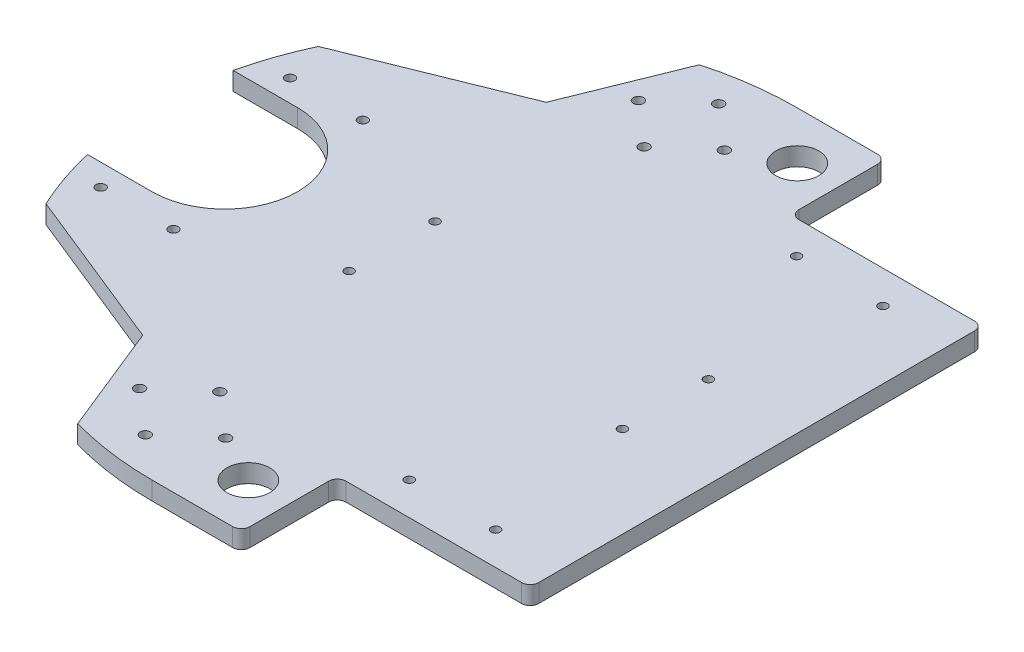
SolidWorks part; units mm, degrees
ref_plane "Front Plane" through (0, 0, 0) normal (0, 0, 1) x (1, 0, 0)
ref_plane "Top Plane" through (0, 0, 0) normal (0, 1, 0) x (1, 0, 0)
ref_plane "Right Plane" through (0, 0, 0) normal (1, 0, 0) x (0, 0, -1)
sketch "Sketch1" plane through (0, 0, 0) normal (0, 1, 0) x (1, 0, 0)
  line L0 (0, -112.5) -> (0, 0) construction
  line L1 (-3.175, 112.5) -> (95.25, 112.5)
  line L3 (-3.175, -112.5) -> (95.25, -112.5)
  line L4 (95.25, 112.5) -> (95.25, -112.5)
  line L5 (0, 0) -> (0, 112.5) construction
  arc A0 (-3.175, 112.5) -> (-3.175, -112.5) centre (-3.175, 0) ccw
  dimension "D1" = 95.25
  dimension "D4" = 112.5
  dimension "D2" = 3.175
  dimension "D3" = 225
extrude "Boss-Extrude1" add sketch "Sketch1" against normal blind 6.35
sketch "Sketch8" plane through (0, 0, 0) normal (0, 1, 0) x (1, 0, 0)
  line L0 (-3.175, 112.5) -> (-3.175, -112.5) construction
  line L1 (-115.675, 0) -> (95.25, 0) construction
  line L2 (95.25, -112.5) -> (95.25, 112.5) construction
  line L3 (-90.2716, 25.4) -> (-229.7767, 25.4)
  line L4 (-229.7767, 25.4) -> (-229.7767, -25.4)
  line L5 (-229.7767, -25.4) -> (-90.2716, -25.4)
  line L6 (-105.3846, 12.065) -> (-105.3846, -12.065) construction
  line L7 (-105.3846, -12.065) -> (-75.1586, -12.065) construction
  line L8 (-75.1586, -12.065) -> (-75.1586, 12.065) construction
  line L9 (-75.1586, 12.065) -> (-105.3846, 12.065) construction
  arc A0 (-3.175, 112.5) -> (-3.175, -112.5) centre (-3.175, 0) ccw construction
  circle A1 centre (-100.5586, 33.02) radius 1.651
  arc A2 (-90.2716, 25.4) -> (-90.2716, -25.4) centre (-90.2716, 0) cw
  circle A3 centre (-100.5586, -33.02) radius 1.651
  circle A4 centre (-75.1586, 33.02) radius 1.651
  circle A5 centre (-75.1586, -33.02) radius 1.651
  point P12 (-3.175, 0)
  point P19 (-75.1586, 0)
  point P22 (-90.2716, 12.065)
  dimension "D2" = 87.0966
  dimension "D1" = 25.4
  dimension "D6" = 33.02
  dimension "D11" = 3.302
  dimension "D3" = 112.5
  dimension "D4" = 30.226
  dimension "D5" = 24.13
  dimension "D7" = 33.02
  dimension "D8" = 33.02
  dimension "D9" = 33.02
  dimension "D10" = 25.4
extrude "Cut-Extrude5" cut sketch "Sketch8" against normal through all
sketch "Sketch9" plane through (0, 0, 0) normal (0, 1, 0) x (1, 0, 0)
  line L0 (-105.1513, 47.5087) -> (-48.5319, 70.3845)
  line L1 (-48.5319, 70.3845) -> (-12.2799, 160.1114)
  line L2 (-19.5468, 160.1114) -> (-135.6404, 160.1114)
  line L3 (-135.6404, 160.1114) -> (-135.6404, 47.5087)
  line L4 (-135.6404, 47.5087) -> (-105.1513, 47.5087)
  line L5 (-12.2799, 160.1114) -> (-19.5468, 160.1114)
  line L6 (-162.9335, 0) -> (171.6729, 0) construction
  line L7 (-105.1513, 0) -> (-105.1513, 47.5087) construction
  line L8 (-105.1513, 47.5087) -> (171.6729, 47.5087) construction
  line L9 (-48.5319, 70.3845) -> (171.6729, 70.3845) construction
  line L10 (-105.1513, -47.5087) -> (-48.5319, -70.3845)
  line L11 (-48.5319, -70.3845) -> (-12.2799, -160.1114)
  line L12 (-12.2799, -160.1114) -> (-135.6404, -160.1114)
  line L13 (-135.6404, -160.1114) -> (-135.6404, -47.5087)
  line L14 (-135.6404, -47.5087) -> (-105.1513, -47.5087)
  line L15 (-105.1513, -47.5087) -> (171.6729, -47.5087) construction
  line L16 (-48.5319, -70.3845) -> (171.6729, -70.3845) construction
  line L17 (-105.1513, -47.5087) -> (-105.1513, 0) construction
  arc A0 (-3.175, 112.5) -> (-112.7701, 25.4) centre (-3.175, 0) ccw construction
  arc A1 (-112.7701, -25.4) -> (-3.175, -112.5) centre (-3.175, 0) ccw construction
  dimension "D1" = 47.5087
  dimension "D2" = 22
  dimension "D3" = 68
  dimension "D4" = 22
  dimension "D5" = 68
extrude "Cut-Extrude6" cut sketch "Sketch9" against normal through all
sketch "Sketch16" plane through (0, 0, 0) normal (0, 1, 0) x (1, 0, 0)
  line L0 (-18, -100) -> (-18, -74) construction
  line L1 (-33, -87) -> (-3, -87) construction
  line L3 (-112.7701, 0) -> (95.25, 0) construction
  line L5 (95.25, -112.5) -> (95.25, 112.5) construction
  circle A0 centre (-33, -87) radius 1.775
  circle A1 centre (-18, -100) radius 1.775
  circle A2 centre (-18, -74) radius 1.775
  circle A3 centre (-3, -87) radius 1.775
  circle A4 centre (-33, 87) radius 1.775
  circle A5 centre (-18, 100) radius 1.775
  circle A6 centre (-18, 74) radius 1.775
  circle A7 centre (-3, 87) radius 1.775
  dimension "D3" = 3.55
  dimension "D1" = 26
  dimension "D2" = 30
  dimension "D4" = 87
  dimension "D5" = 113.25
extrude "Cut-Extrude9" cut sketch "Sketch16" against normal through all
sketch "Sketch17" plane through (0, 0, 0) normal (0, 1, 0) x (1, 0, 0)
  line L0 (95.25, 0) -> (-112.7701, 0) construction
  line L1 (95.25, 112.5) -> (27.98, 112.5)
  line L2 (95.25, 112.5) -> (95.25, 79)
  line L3 (95.25, 79) -> (27.98, 79)
  line L4 (27.98, 112.5) -> (27.98, 79)
  line L5 (95.25, -112.5) -> (27.98, -112.5)
  line L6 (95.25, -112.5) -> (95.25, -79)
  line L7 (95.25, -79) -> (27.98, -79)
  line L8 (27.98, -112.5) -> (27.98, -79)
  line L9 (95.25, -112.5) -> (95.25, 112.5) construction
  line L10 (41.62, -67.5582) -> (41.62, 67.5582) construction
  line L11 (41.62, 67.5582) -> (71.75, 67.5582) construction
  line L12 (71.75, 67.5582) -> (71.75, -67.5582) construction
  line L13 (71.75, -67.5582) -> (41.62, -67.5582) construction
  line L14 (27.98, 95.75) -> (95.25, 95.75) construction
  line L15 (27.98, -95.75) -> (95.25, -95.75) construction
  circle A0 centre (41.62, 67.5582) radius 1.55
  circle A1 centre (71.75, 67.5582) radius 1.55
  circle A2 centre (41.62, -67.5582) radius 1.55
  circle A3 centre (71.75, -67.5582) radius 1.55
  circle A4 centre (13.6873, 95.75) radius 7.5
  circle A5 centre (13.6873, -95.75) radius 7.5
  dimension "D4" = 3.1
  dimension "D5" = 15
  dimension "D1" = 33.5
  dimension "D2" = 30.13
  dimension "D3" = 23.5
extrude "Cut-Extrude10" cut sketch "Sketch17" against normal through all
fillet "Fillet1" radius 3 6 edges at (27.98, -3.175, -112.5) (27.98, -3.175, -79) (95.25, -3.175, -79) (95.25, -3.175, 79) (27.98, -3.175, 79) (27.98, -3.175, 112.5)
sketch "Sketch18" plane through (0, 0, 0) normal (0, 1, 0) x (1, 0, 0)
  line L0 (-31.9194, 15) -> (63.4406, 15) construction
  line L1 (63.4406, 15) -> (63.4406, -15) construction
  line L2 (63.4406, -15) -> (-31.9194, -15) construction
  line L3 (-31.9194, -15) -> (-31.9194, 15) construction
  line L4 (95.25, 0) -> (-112.7701, 0) construction
  line L5 (95.25, -76) -> (95.25, 76) construction
  circle A1 centre (-31.9194, 15) radius 1.55
  circle A2 centre (-31.9194, -15) radius 1.55
  circle A3 centre (63.4406, 15) radius 1.55
  circle A4 centre (63.4406, -15) radius 1.55
  dimension "D3" = 3.1
  dimension "D1" = 95.36
  dimension "D2" = 30
extrude "Cut-Extrude11" cut sketch "Sketch18" against normal through all
